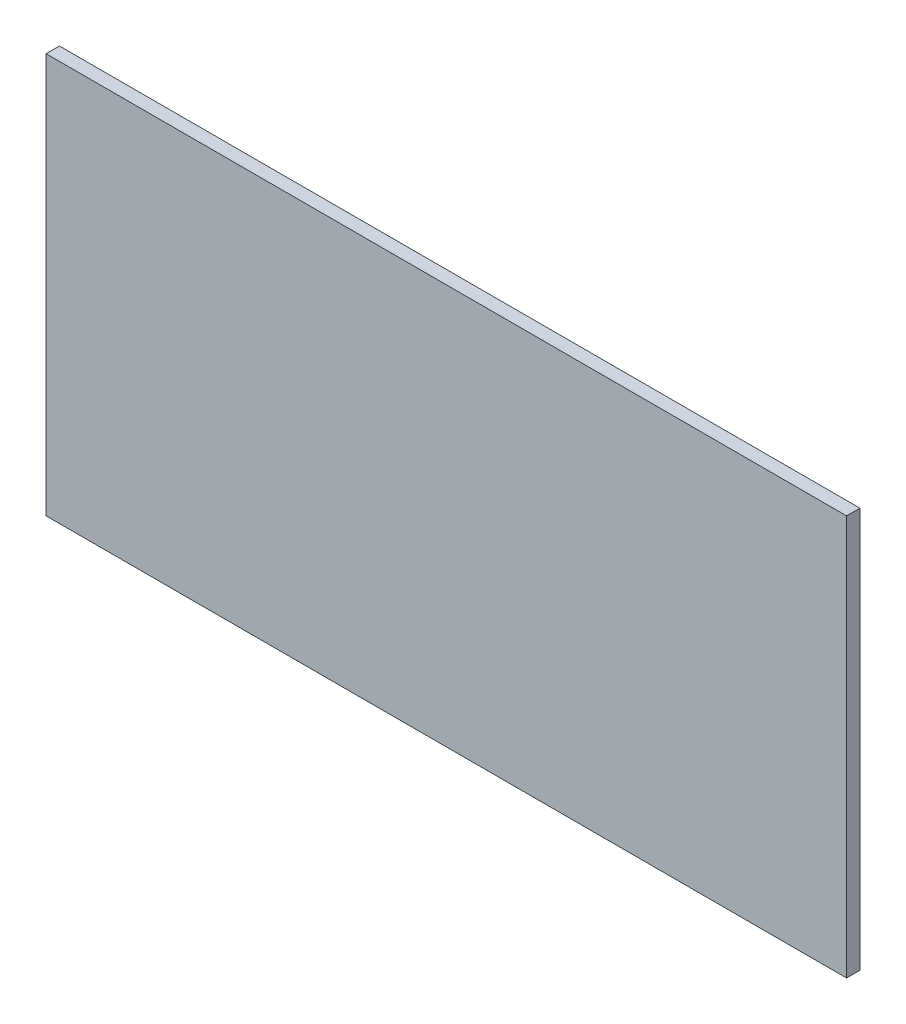
SolidWorks part; units mm, degrees
ref_plane "Plan de face" through (0, 0, 0) normal (0, 0, 1) x (1, 0, 0)
ref_plane "Plan de dessus" through (0, 0, 0) normal (0, 1, 0) x (1, 0, 0)
ref_plane "Plan de droite" through (0, 0, 0) normal (1, 0, 0) x (0, 0, -1)
sketch "Esquisse1" plane through (0, 0, 0) normal (0, 0, 1) x (1, 0, 0)
  line L1 (-150, 75) -> (150, 75)
  line L2 (-150, 75) -> (-150, -75)
  line L3 (-150, -75) -> (150, -75)
  line L4 (150, 75) -> (150, -75)
  line L5 (-150, 75) -> (150, -75) construction
  line L6 (-150, -75) -> (150, 75) construction
  point P0 (0, 0)
  dimension "D1" = 300
  dimension "D2" = 150
extrude "Boss.-Extru.1" add sketch "Esquisse1" along normal blind 5
